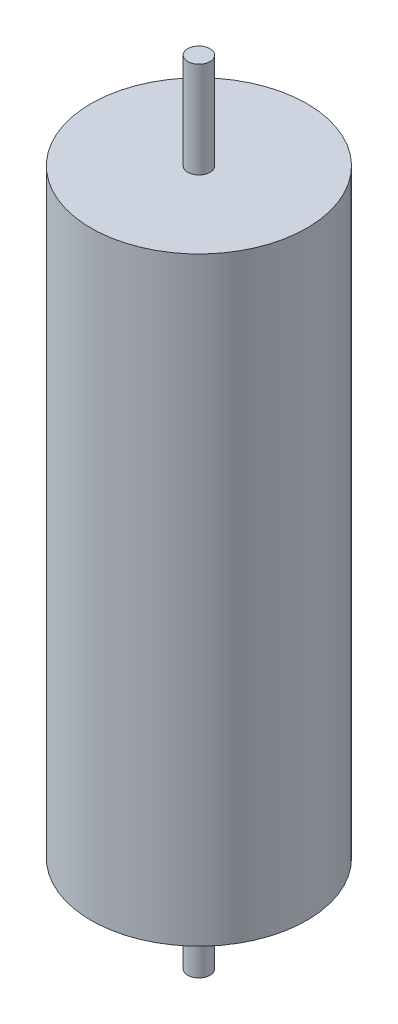
SolidWorks part; units mm, degrees
ref_plane "Front Plane" through (0, 0, 0) normal (0, 0, 1) x (1, 0, 0)
ref_plane "Top Plane" through (0, 0, 0) normal (0, 1, 0) x (1, 0, 0)
ref_plane "Right Plane" through (0, 0, 0) normal (1, 0, 0) x (0, 0, -1)
sketch "Sketch1" plane through (0, 0, 0) normal (0, 1, 0) x (1, 0, 0)
  circle A0 centre (0, 0) radius 114.3
  dimension "D1" = 228.6
extrude "Boss-Extrude1" add sketch "Sketch1" along normal mid plane 635
sketch "Sketch2" plane through (0, 317.5, 0) normal (0, 1, 0) x (1, 0, 0)
  circle A0 centre (0, 0) radius 11.811
  dimension "D1" = 23.622
extrude "Boss-Extrude2" add sketch "Sketch2" along normal blind 101.6
sketch "Sketch3" plane through (0, -317.5, 0) normal (0, -1, 0) x (1, 0, 0)
  circle A0 centre (0, 0) radius 11.811
  dimension "D1" = 23.622
extrude "Boss-Extrude3" add sketch "Sketch3" along normal blind 101.6
